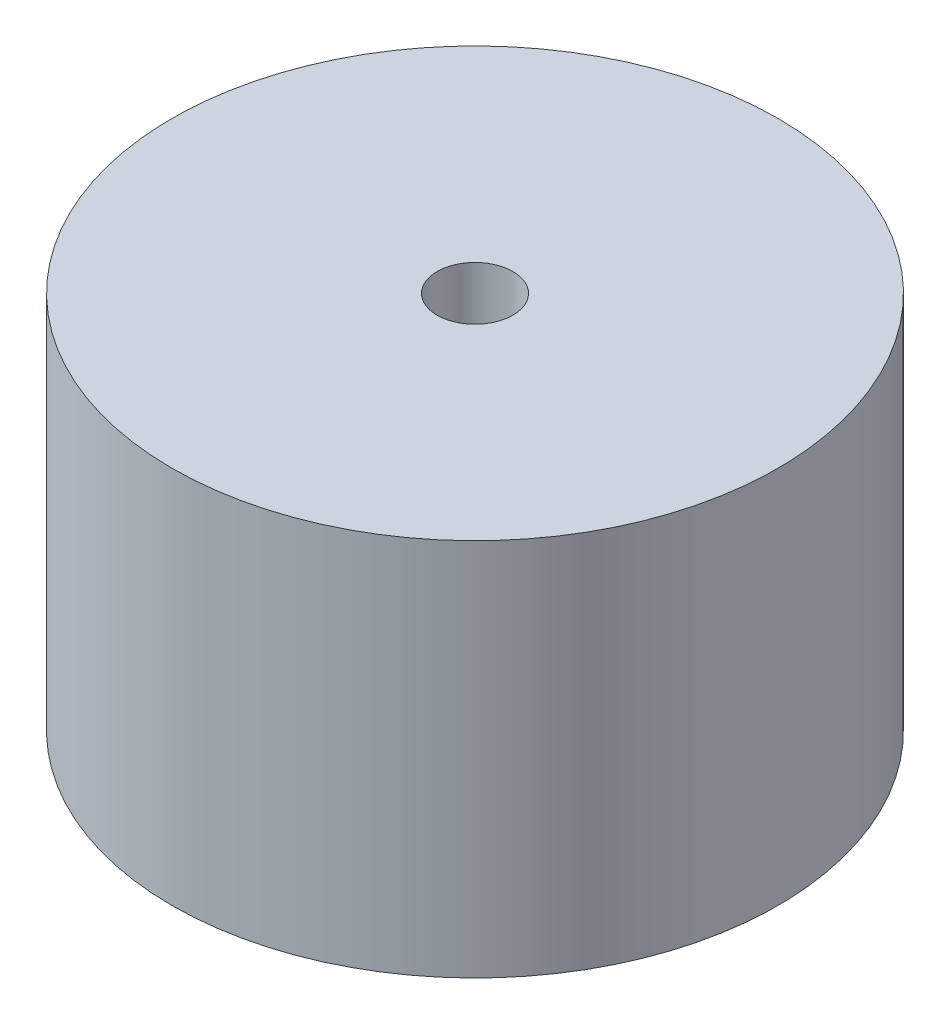
SolidWorks part; units mm, degrees
ref_plane "前视基准面" through (0, 0, 0) normal (0, 0, 1) x (1, 0, 0)
ref_plane "上视基准面" through (0, 0, 0) normal (0, 1, 0) x (1, 0, 0)
ref_plane "右视基准面" through (0, 0, 0) normal (1, 0, 0) x (0, 0, -1)
other "Configuration Table"
sketch "草图1" plane through (0, 0, 0) normal (0, 1, 0) x (1, 0, 0)
  circle A0 centre (0, 0) radius 40
  circle A1 centre (0, 0) radius 5
  dimension "D1" = 80
  dimension "D2" = 10
extrude "凸台-拉伸1" add sketch "草图1" along normal blind 50
sketch "草图2" plane through (0, 50, 0) normal (0, 1, 0) x (1, 0, 0)
  line L1 (-6.5826, 2) -> (-4.5826, 2)
  line L2 (-6.5826, 2) -> (-6.5826, -2)
  line L3 (-6.5826, -2) -> (-4.5826, -2)
  line L4 (-4.5826, 2) -> (-4.5826, -2)
  line L5 (-6.5826, 2) -> (-4.5826, -2) construction
  line L6 (-6.5826, -2) -> (-4.5826, 2) construction
  circle A1 centre (0, 0) radius 5 construction
  point P0 (-5.5826, 0)
  point P5 (0, 0)
  point P7 (0, 0)
  point P8 (-1.5833, 4.7427)
  point P10 (-2.0641, 4.0722)
  dimension "D1" = 2
  dimension "D2" = 4
